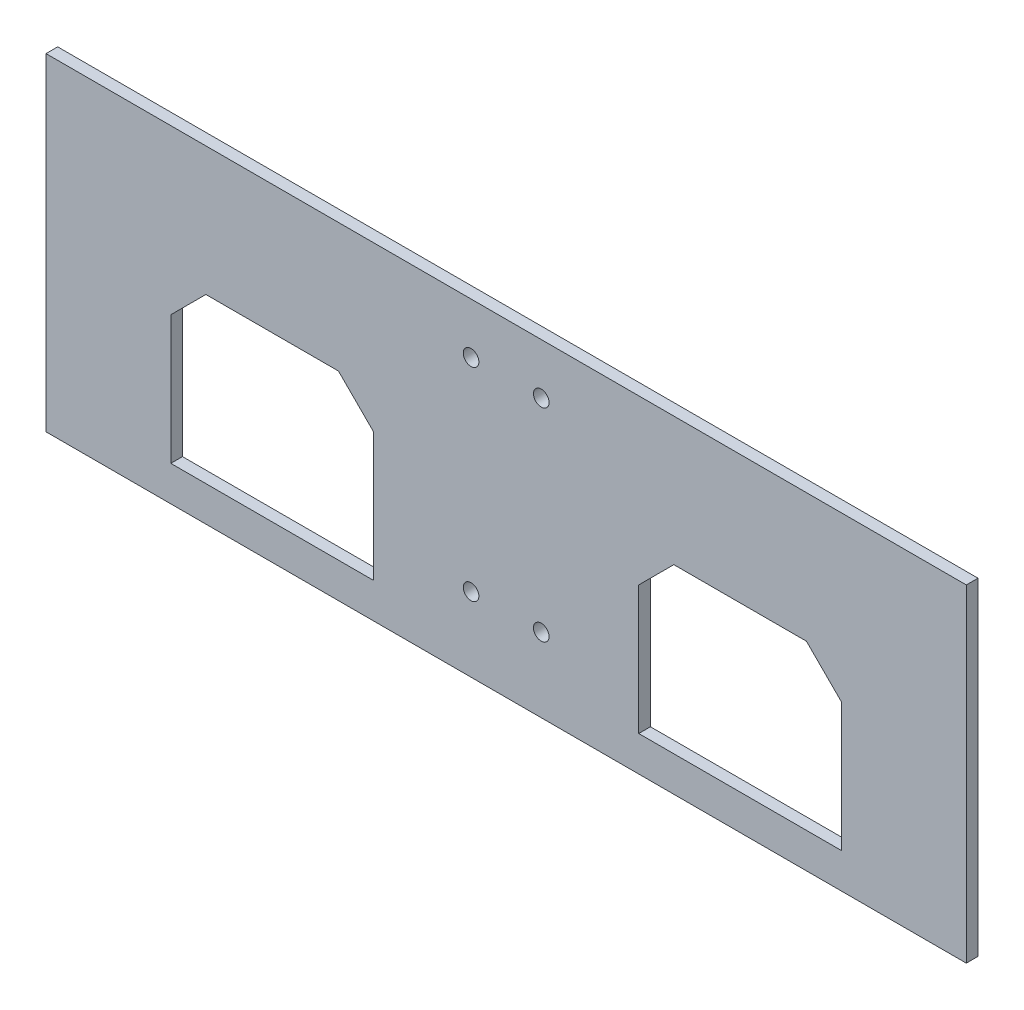
SolidWorks part; units mm, degrees
ref_plane "Plan de face" through (0, 0, 0) normal (0, 0, 1) x (1, 0, 0)
ref_plane "Plan de dessus" through (0, 0, 0) normal (0, 1, 0) x (1, 0, 0)
ref_plane "Plan de droite" through (0, 0, 0) normal (1, 0, 0) x (0, 0, -1)
sketch "Esquisse1" plane through (0, 0, 0) normal (0, 0, 1) x (1, 0, 0)
  line L0 (0, 0) -> (118, 0) construction
  line L1 (0, 0) -> (-118, 0) construction
  line L2 (-118, 0) -> (-118, 39) construction
  line L3 (-118, 39) -> (118, 39)
  line L4 (118, 39) -> (118, -39)
  line L5 (118, -39) -> (-118, -39)
  line L7 (-118, 39) -> (-118, -39)
  dimension "D1" = 39
  dimension "D2" = 118
  dimension "D4" = 78
extrude "Boss.-Extru.1" add sketch "Esquisse1" along normal blind 3
sketch "Esquisse2" plane through (0, 0, 3) normal (0, 0, 1) x (1, 0, 0)
  line L0 (0, -39) -> (0, -26) construction
  line L1 (-118, -39) -> (118, -39) construction
  line L2 (0, -26) -> (9, -26) construction
  line L3 (0, -26) -> (-9, -26) construction
  circle A0 centre (9, -26) radius 2
  circle A1 centre (-9, -26) radius 2
  dimension "D1" = 13
extrude "Enlèv. mat.-Extru.1" cut sketch "Esquisse2" against normal up to next
mirror "Symétrie1" about plane through (0, 0, 0) normal (0, 1, 0) of "Enlèv. mat.-Extru.1"
sketch "Esquisse3" plane through (0, 0, 3) normal (0, 0, 1) x (1, 0, 0)
  line L0 (-118, -39) -> (-118, -45)
  line L1 (-118, -45) -> (118, -45)
  line L2 (118, -39) -> (118, -45)
  line L4 (118, -39) -> (-118, -39)
extrude "Boss.-Extru.2" add sketch "Esquisse3" against normal blind 3
sketch "Esquisse4" plane through (0, 0, 3) normal (0, 0, 1) x (1, 0, 0)
  line L0 (0, -45) -> (0, -36) construction
  line L1 (-118, -45) -> (118, -45) construction
  line L2 (-34, -36) -> (34, -36) construction
  line L3 (34, -36) -> (34, -3)
  line L4 (34, -3) -> (43, -3) construction
  line L5 (43, -3) -> (43, 6) construction
  line L6 (43, 6) -> (77, 6)
  line L7 (34, -3) -> (43, 6)
  line L8 (34, -36) -> (86, -36)
  line L9 (86, -36) -> (86, -3)
  line L10 (86, -3) -> (77, -3) construction
  line L11 (77, -3) -> (77, 6) construction
  line L12 (86, -3) -> (77, 6)
  line L13 (0, -1.65) -> (0, 1.65) construction
  line L14 (-77, -3) -> (-77, 6) construction
  line L15 (-86, -3) -> (-77, -3) construction
  line L16 (-43, -3) -> (-43, 6) construction
  line L17 (-34, -3) -> (-43, -3) construction
  line L18 (-86, -3) -> (-77, 6)
  line L19 (-86, -36) -> (-86, -3)
  line L20 (-34, -36) -> (-86, -36)
  line L21 (-34, -3) -> (-43, 6)
  line L22 (-43, 6) -> (-77, 6)
  line L23 (-34, -36) -> (-34, -3)
  dimension "D1" = 9
  dimension "D2" = 34
  dimension "D3" = 33
  dimension "D4" = 9
  dimension "D5" = 9
  dimension "D6" = 34
  dimension "D7" = 33
  dimension "D8" = 9
  dimension "D9" = 9
extrude "Enlèv. mat.-Extru.2" cut sketch "Esquisse4" against normal up to next
